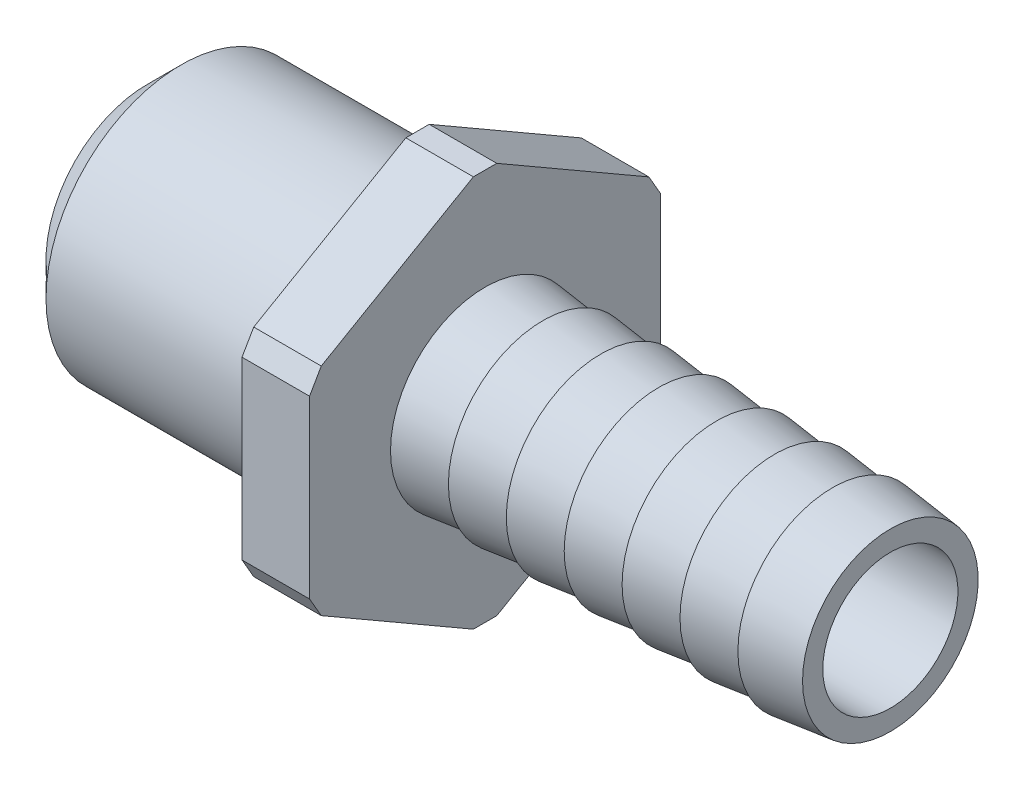
SolidWorks part; units mm, degrees
material "Brass"
ref_plane "Front Plane" through (0, 0, 0) normal (0, 0, 1) x (1, 0, 0)
ref_plane "Top Plane" through (0, 0, 0) normal (0, 1, 0) x (1, 0, 0)
ref_plane "Right Plane" through (0, 0, 0) normal (1, 0, 0) x (0, 0, -1)
sketch "Sketch1" plane through (0, 0, 0) normal (0, 0, 1) x (1, 0, 0)
  line L0 (0, 1) -> (11, 1)
  line L1 (0, 2) -> (4, 2)
  line L2 (0, 1) -> (0, 2)
  line L3 (11, 1.3) -> (11, 1)
  line L4 (4, 2) -> (4, 3)
  line L5 (4, 3) -> (5, 3)
  line L6 (5, 3) -> (5, 1.4)
  line L8 (0, 0) -> (11.3598, 0) construction
  line L9 (11, 1.3) -> (10.1429, 1.4)
  line L10 (10.1429, 1.4) -> (10.1429, 1.3)
  line L11 (10.1429, 1.3) -> (9.2857, 1.4)
  line L12 (9.2857, 1.4) -> (9.2857, 1.3)
  line L13 (9.2857, 1.3) -> (8.4286, 1.4)
  line L14 (8.4286, 1.4) -> (8.4286, 1.3)
  line L15 (8.4286, 1.3) -> (7.5714, 1.4)
  line L16 (7.5714, 1.4) -> (7.5714, 1.3)
  line L17 (7.5714, 1.3) -> (6.7143, 1.4)
  line L18 (6.7143, 1.4) -> (6.7143, 1.3)
  line L19 (6.7143, 1.3) -> (5.8571, 1.4)
  line L20 (5.8571, 1.4) -> (5.8571, 1.3)
  line L21 (5.8571, 1.3) -> (5, 1.4)
  point P3 (5, 0)
  dimension "D1" = 11
  dimension "D2" = 2
  dimension "D3" = 1
  dimension "D4" = 2
  dimension "D5" = 1
  dimension "D6" = 4
  dimension "D7" = 0.3
  dimension "D8" = 1.4
revolve "Revolve1" add sketch "Sketch1" angle 360 about L8
cosmetic thread "Cosmetic Thread1" parameters "D2"=3.22
chamfer "Chamfer1" distance 0.5 angle 45 1 edges at (0, 0, 2)
sketch "Sketch2" plane through (4, 0, 0) normal (-1, 0, 0) x (0, 0, 1)
  line L0 (0, 0) -> (2.5981, 1.5) construction
  line L1 (0, 3) -> (-2.5981, 1.5)
  line L2 (-2.5981, 1.5) -> (-2.5981, -1.5)
  line L3 (-2.5981, -1.5) -> (0, -3)
  line L4 (0, -3) -> (2.5981, -1.5)
  line L5 (2.5981, -1.5) -> (2.5981, 1.5)
  line L6 (2.5981, 1.5) -> (0, 3)
  line L7 (0, 0) -> (0, 3) construction
  circle A0 centre (0, 0) radius 2.5981 construction
  circle A1 centre (0, 0) radius 6
  circle A2 centre (0, 0) radius 3 construction
  point P10 (0, -6)
  dimension "D2" = 12
extrude "Cut-Extrude2" cut sketch "Sketch2" against normal through all
chamfer "Chamfer2" distance 0.2 6 edges at (4.5, 1.5, -2.5981) (4.5, -1.5, -2.5981) (4.5, -3, 0) (4.5, -1.5, 2.5981) (4.5, 3, 0) (4.5, 1.5, 2.5981)
